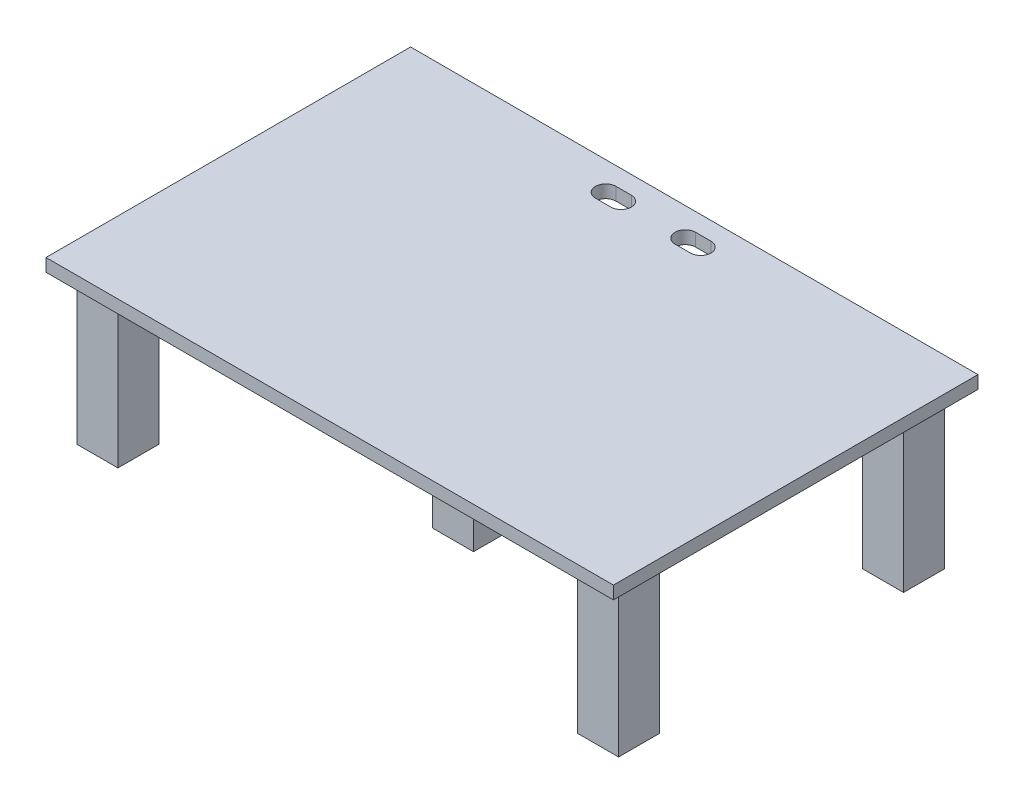
SolidWorks part; units mm, degrees
ref_plane "前视基准面" through (0, 0, 0) normal (0, 0, 1) x (1, 0, 0)
ref_plane "上视基准面" through (0, 0, 0) normal (0, 1, 0) x (1, 0, 0)
ref_plane "右视基准面" through (0, 0, 0) normal (1, 0, 0) x (0, 0, -1)
other "Configuration Table"
ref_plane "V4_upper_top_y_plus4" through (0, 4, 0) normal (0, 1, 0) x (1, 0, 0)
ref_plane "V4_upper_underside_y_minus1" through (0, -1, 0) normal (0, 1, 0) x (1, 0, 0)
ref_plane "V4_post_bottom_y_minus60" through (0, -60, 0) normal (0, 1, 0) x (1, 0, 0)
sketch "V4_upper_deck_221x142_profile" plane through (0, 4, 0) normal (0, 1, 0) x (1, 0, 0)
  line L1 (-98, -44) -> (123, -44)
  line L2 (-98, -44) -> (-98, -186)
  line L3 (-98, -186) -> (123, -186)
  line L4 (123, -44) -> (123, -186)
extrude "V4_upper_deck_5mm" add sketch "V4_upper_deck_221x142_profile" against normal blind 5
sketch "V4_five_support_posts_profile" plane through (0, -1, 0) normal (0, 1, 0) x (1, 0, 0)
  line L1 (-93, -52) -> (-77, -52)
  line L2 (-93, -52) -> (-93, -68)
  line L3 (-93, -68) -> (-77, -68)
  line L4 (-77, -52) -> (-77, -68)
  line L6 (102, -52) -> (118, -52)
  line L7 (102, -52) -> (102, -68)
  line L8 (102, -68) -> (118, -68)
  line L9 (118, -52) -> (118, -68)
  line L11 (-93, -163) -> (-77, -163)
  line L12 (-93, -163) -> (-93, -179)
  line L13 (-93, -179) -> (-77, -179)
  line L14 (-77, -163) -> (-77, -179)
  line L16 (102, -163) -> (118, -163)
  line L17 (102, -163) -> (102, -179)
  line L18 (102, -179) -> (118, -179)
  line L19 (118, -163) -> (118, -179)
  line L21 (4.5, -122) -> (20.5, -122)
  line L22 (4.5, -122) -> (4.5, -138)
  line L23 (4.5, -138) -> (20.5, -138)
  line L24 (20.5, -122) -> (20.5, -138)
extrude "V4_five_support_posts_59mm" add sketch "V4_five_support_posts_profile" against normal blind 59
sketch "V4_upper_two_cable_slots_profile" plane through (0, 4, 0) normal (0, 1, 0) x (1, 0, 0)
  line L0 (-11, -55) -> (-5, -55) construction
  line L1 (-11, -51) -> (-5, -51)
  line L2 (-11, -59) -> (-5, -59)
  line L3 (20, -55) -> (26, -55) construction
  line L4 (20, -51) -> (26, -51)
  line L5 (20, -59) -> (26, -59)
  arc A0 (-11, -51) -> (-11, -59) centre (-11, -55) ccw
  arc A1 (-5, -59) -> (-5, -51) centre (-5, -55) ccw
  arc A2 (20, -51) -> (20, -59) centre (20, -55) ccw
  arc A3 (26, -59) -> (26, -51) centre (26, -55) ccw
  point P2 (-8, -55)
  point P7 (23, -55)
  point P14 (0, 0)
  dimension "D1" = 8
  dimension "D2" = 6
  dimension "D3" = 8
  dimension "D4" = 6
extrude "V4_upper_two_cable_slots" cut sketch "V4_upper_two_cable_slots_profile" against normal blind 5.5
sketch "V4_five_M3_pilots_profile" plane through (0, -60, 0) normal (0, 1, 0) x (1, 0, 0)
  circle A0 centre (-85, -60) radius 1.4
  circle A1 centre (110, -60) radius 1.4
  circle A2 centre (-85, -171) radius 1.4
  circle A3 centre (110, -171) radius 1.4
  circle A4 centre (12.5, -130) radius 1.4
extrude "V4_post_pilot_holes" cut sketch "V4_five_M3_pilots_profile" along normal blind 14
